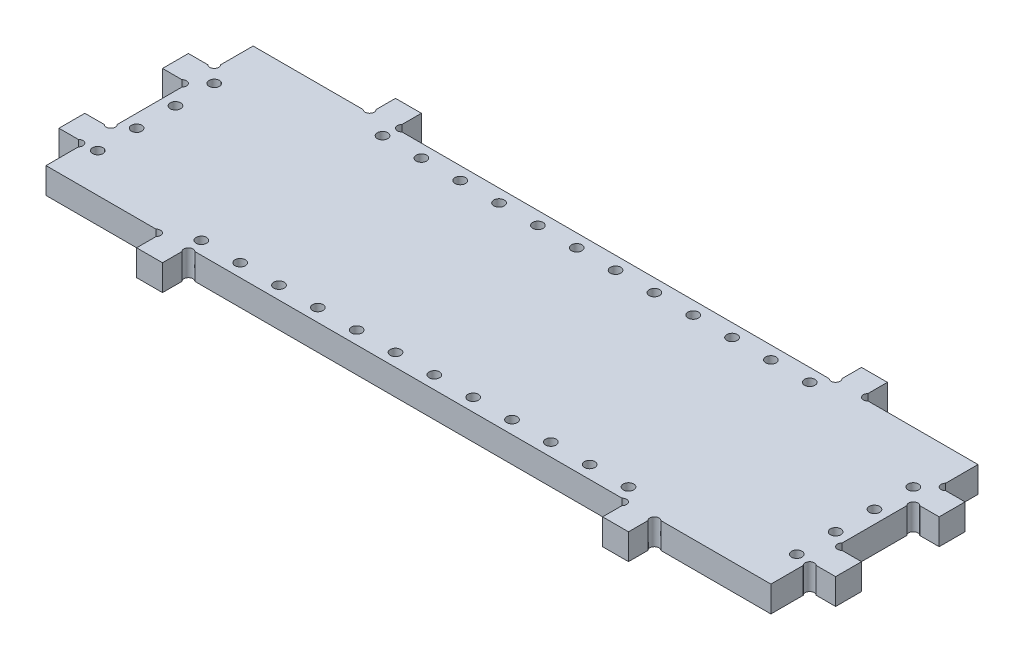
SolidWorks part; units mm, degrees
material "6061 Alloy"
ref_plane "Front" through (0, 0, 0) normal (0, 0, 1) x (1, 0, 0)
ref_plane "Top" through (0, 0, 0) normal (0, 1, 0) x (1, 0, 0)
ref_plane "Right" through (0, 0, 0) normal (1, 0, 0) x (0, 0, -1)
sketch "Sketch2" plane through (0, 0, 0) normal (0, 1, 0) x (1, 0, 0)
  line L1 (-177.8, -50.8) -> (177.8, -50.8)
  line L2 (-177.8, -50.8) -> (-177.8, 50.8)
  line L3 (-177.8, 50.8) -> (177.8, 50.8)
  line L4 (177.8, -50.8) -> (177.8, 50.8)
  line L5 (-177.8, -50.8) -> (177.8, 50.8) construction
  line L6 (-177.8, 50.8) -> (177.8, -50.8) construction
  point P0 (0, 0)
  dimension "D1" = 355.6
  dimension "D2" = 101.6
extrude "Rectangle Extrusion" add sketch "Sketch2" along normal blind 12.7
sketch "Sketch4" plane through (0, 0, 50.8) normal (0, 0, 1) x (1, 0, 0)
  line L0 (-177.8, 12.7) -> (-114.3, 12.7) construction
  line L1 (-177.8, 12.7) -> (177.8, 12.7) construction
  line L2 (-114.3, 12.7) -> (-114.3, 6.35) construction
  line L3 (-177.8, 0) -> (177.8, 0) construction
  line L4 (-107.95, 12.7) -> (-120.65, 12.7)
  line L5 (-107.95, 12.7) -> (-107.95, 0)
  line L6 (-107.95, 0) -> (-120.65, 0)
  line L7 (-120.65, 12.7) -> (-120.65, 0)
  line L8 (-107.95, 12.7) -> (-120.65, 0) construction
  line L9 (-107.95, 0) -> (-120.65, 12.7) construction
  line L10 (0, 12.7) -> (0, 0) construction
  line L11 (107.95, 0) -> (120.65, 0)
  line L12 (120.65, 12.7) -> (120.65, 0)
  line L13 (107.95, 12.7) -> (120.65, 12.7)
  line L14 (107.95, 12.7) -> (107.95, 0)
  dimension "D1" = 63.5
  dimension "D2" = 6.35
  dimension "D3" = 12.7
extrude "Front Face Tabs" add sketch "Sketch4" along normal blind 12.7
mirror "Mirror Rear Face Tabs" about plane through (0, 0, 0) normal (0, 0, 1) of "Front Face Tabs"
sketch "Sketch6" plane through (0, 12.7, 0) normal (0, 1, 0) x (1, 0, 0)
  line L0 (-120.65, 50.8) -> (-177.8, 50.8) construction
  line L1 (-120.65, 63.5) -> (-120.65, 50.8) construction
  line L2 (-114.3, 63.5) -> (-114.3, 50.1421) construction
  line L3 (-107.95, 63.5) -> (-120.65, 63.5) construction
  line L4 (0, -55) -> (0, 55) construction
  line L5 (-55, 0) -> (55, 0) construction
  circle A0 centre (-122.2375, 52.3875) radius 2.2454
  circle A1 centre (-106.3625, 52.3875) radius 2.2454
  circle A2 centre (106.3625, 52.3875) radius 2.2454
  circle A3 centre (122.2375, 52.3875) radius 2.2454
  circle A4 centre (122.2375, -52.3875) radius 2.2454
  circle A5 centre (106.3625, -52.3875) radius 2.2454
  circle A6 centre (-106.3625, -52.3875) radius 2.2454
  circle A7 centre (-122.2375, -52.3875) radius 2.2454
  dimension "D1" = 1.5875
  dimension "D3" = 4.4907
  dimension "D2" = 1.5875
extrude "Tab Curve Front Back" cut sketch "Sketch6" against normal up to surface (12.7 mm away) up to face at (0, 0, 0)
sketch "Sketch7" plane through (177.8, 0, 0) normal (1, 0, 0) x (0, 0, -1)
  line L0 (-50.8, 12.7) -> (-25.4, 12.7) construction
  line L1 (-50.8, 12.7) -> (50.8, 12.7) construction
  line L2 (-25.4, 12.7) -> (-25.4, 0) construction
  line L3 (55, 0) -> (-55, 0) construction
  line L4 (0, 55) -> (0, -55) construction
  line L5 (-31.75, 12.7) -> (-19.05, 12.7)
  line L6 (-31.75, 12.7) -> (-31.75, 0)
  line L7 (-31.75, 0) -> (-19.05, 0)
  line L8 (-19.05, 12.7) -> (-19.05, 0)
  line L9 (-31.75, 12.7) -> (-19.05, 0) construction
  line L10 (-31.75, 0) -> (-19.05, 12.7) construction
  line L11 (31.75, 0) -> (19.05, 0)
  line L12 (19.05, 12.7) -> (19.05, 0)
  line L13 (31.75, 12.7) -> (19.05, 12.7)
  line L14 (31.75, 12.7) -> (31.75, 0)
  point P5 (-25.4, 6.35)
  dimension "D1" = 25.4
  dimension "D2" = 12.7
extrude "Right Face Tabs" add sketch "Sketch7" along normal blind 12.7
mirror "Mirror Left Face Tabs" about plane through (0, 0, 0) normal (1, 0, 0) of "Right Face Tabs"
sketch "Sketch8" plane through (0, 12.7, 0) normal (0, 1, 0) x (1, 0, 0)
  line L0 (190.5, 31.75) -> (177.8, 31.75) construction
  line L1 (177.8, 31.75) -> (177.8, 50.8) construction
  line L2 (190.5, 25.4) -> (126.2032, 25.4) construction
  line L3 (190.5, 31.75) -> (190.5, 19.05) construction
  line L4 (-55, 0) -> (55, 0) construction
  line L5 (0, -55) -> (0, 55) construction
  circle A0 centre (179.3875, 33.3375) radius 2.2454
  circle A1 centre (179.3875, 17.4625) radius 2.2454
  circle A2 centre (179.3875, -17.4625) radius 2.2454
  circle A3 centre (179.3875, -33.3375) radius 2.2454
  circle A4 centre (-179.3875, -33.3375) radius 2.2454
  circle A5 centre (-179.3875, -17.4625) radius 2.2454
  circle A6 centre (-179.3875, 17.4625) radius 2.2454
  circle A7 centre (-179.3875, 33.3375) radius 2.2454
  dimension "D3" = 4.4907
  dimension "D1" = 1.5875
  dimension "D2" = 1.5875
extrude "Tab Curve Left Right" cut sketch "Sketch8" against normal up to surface (12.7 mm away) up to face at (0, 0, 0)
sketch "Sketch9" plane through (0, 0, 0) normal (0, -1, 0) x (1, 0, 0)
  line L0 (-177.8, 44.45) -> (177.8, 44.45) construction
  line L1 (-177.8, 34.9254) -> (-177.8, 50.8) construction
  line L2 (177.8, 50.8) -> (177.8, 34.9254) construction
  line L3 (-177.8, 50.8) -> (-123.8254, 50.8) construction
  line L4 (-177.8, 0) -> (177.8, 0) construction
  line L5 (-177.8, -15.8746) -> (-177.8, 15.8746) construction
  line L6 (177.8, 15.8746) -> (177.8, -15.8746) construction
  line L7 (171.45, 50.8) -> (171.45, -50.8) construction
  line L8 (123.8254, 50.8) -> (177.8, 50.8) construction
  line L9 (177.8, -50.8) -> (123.8254, -50.8) construction
  line L10 (0, 50.8) -> (0, -50.8) construction
  line L11 (-104.7746, 50.8) -> (104.7746, 50.8) construction
  line L12 (104.7746, -50.8) -> (-104.7746, -50.8) construction
  circle A0 centre (-107.95, 44.45) radius 2.5527
  circle A32 centre (-88.9, 44.45) radius 2.5527
  circle A33 centre (-69.85, 44.45) radius 2.5527
  circle A34 centre (-50.8, 44.45) radius 2.5527
  circle A35 centre (-31.75, 44.45) radius 2.5527
  circle A36 centre (-12.7, 44.45) radius 2.5527
  circle A37 centre (6.35, 44.45) radius 2.5527
  circle A38 centre (25.4, 44.45) radius 2.5527
  circle A39 centre (44.45, 44.45) radius 2.5527
  circle A40 centre (63.5, 44.45) radius 2.5527
  circle A41 centre (82.55, 44.45) radius 2.5527
  circle A42 centre (101.6, 44.45) radius 2.5527
  circle A43 centre (101.6, -44.45) radius 2.5527
  circle A44 centre (82.55, -44.45) radius 2.5527
  circle A45 centre (63.5, -44.45) radius 2.5527
  circle A46 centre (44.45, -44.45) radius 2.5527
  circle A47 centre (25.4, -44.45) radius 2.5527
  circle A48 centre (6.35, -44.45) radius 2.5527
  circle A49 centre (-12.7, -44.45) radius 2.5527
  circle A50 centre (-31.75, -44.45) radius 2.5527
  circle A51 centre (-50.8, -44.45) radius 2.5527
  circle A52 centre (-69.85, -44.45) radius 2.5527
  circle A53 centre (-88.9, -44.45) radius 2.5527
  circle A54 centre (-107.95, -44.45) radius 2.5527
  circle A55 centre (171.45, -25.4) radius 2.5527
  circle A56 centre (171.45, -6.35) radius 2.5527
  circle A57 centre (171.45, 12.7) radius 2.5527
  circle A58 centre (171.45, 31.75) radius 2.5527
  circle A59 centre (-171.45, -25.4) radius 2.5527
  circle A60 centre (-171.45, -6.35) radius 2.5527
  circle A61 centre (-171.45, 12.7) radius 2.5527
  circle A62 centre (-171.45, 31.75) radius 2.5527
  point P64 (-127, 50.8)
  dimension "D2" = 69.85
  dimension "D3" = 5.1054
  dimension "D5" = 19.05
  dimension "D7" = 25.4
  dimension "D8" = 5.1054
  dimension "D10" = 19.05
  dimension "D1" = 6.35
  dimension "D6" = 6.35
  dimension "D4" = 12
  dimension "D9" = 4
extrude "Cut-Extrude1" cut sketch "Sketch9" against normal through all
